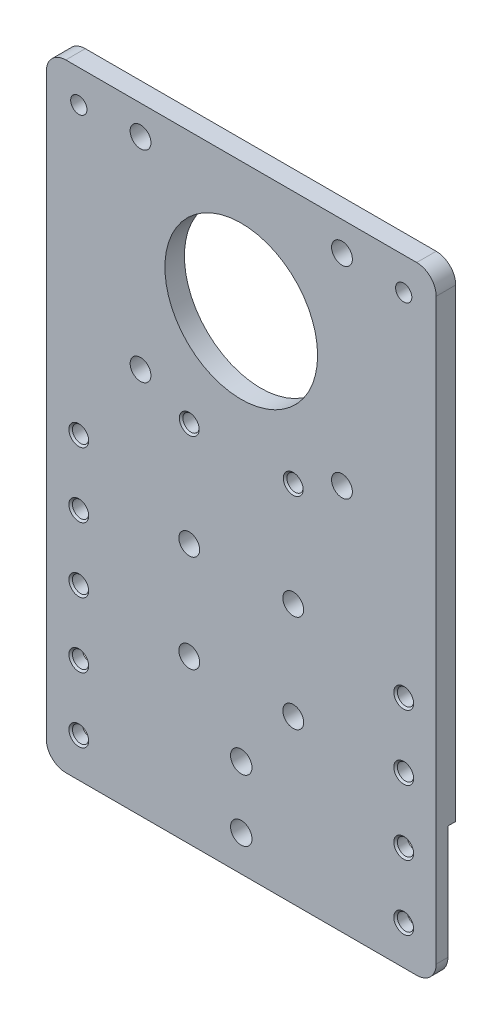
SolidWorks part; units mm, degrees
ref_plane "前视基准面" through (0, 0, 0) normal (0, 0, 1) x (1, 0, 0)
ref_plane "上视基准面" through (0, 0, 0) normal (0, 1, 0) x (1, 0, 0)
ref_plane "右视基准面" through (0, 0, 0) normal (1, 0, 0) x (0, 0, -1)
sketch "草图1" plane through (0, 0, 0) normal (0, 0, 1) x (1, 0, 0)
  line L0 (-30, -25) -> (-30, -67)
  line L1 (-27, 25) -> (27, 25)
  line L2 (-30, 22) -> (-30, -25)
  line L3 (-27, -70) -> (27, -70)
  line L4 (30, 22) -> (30, -67)
  circle A6 centre (0, 5) radius 11.75
  circle A7 centre (15.5, 20.5) radius 1.6
  circle A8 centre (-15.5, 20.5) radius 1.6
  circle A9 centre (-15.5, -10.5) radius 1.6
  circle A10 centre (15.5, -10.5) radius 1.6
  arc A11 (-30, -67) -> (-27, -70) centre (-27, -67) ccw
  arc A12 (27, -70) -> (30, -67) centre (27, -67) ccw
  arc A13 (27, 25) -> (30, 22) centre (27, 22) cw
  arc A14 (-27, 25) -> (-30, 22) centre (-27, 22) ccw
  circle A15 centre (-8, -30) radius 1.6
  circle A16 centre (8, -30) radius 1.6
  circle A17 centre (-8, -45) radius 1.6
  circle A18 centre (8, -45) radius 1.6
  point P47 (-30, -70)
  point P52 (30, 25)
  point P55 (-30, 25)
  dimension "D14" = 23.5
  dimension "D17" = 3.2
  dimension "D22" = 3.2
  dimension "D23" = 3.2
  dimension "D24" = 3.2
  dimension "D25" = 3
  dimension "D26" = 3.2
  dimension "D1" = 95
  dimension "D2" = 60
  dimension "D3" = 25
  dimension "D4" = 30
  dimension "D16" = 20
  dimension "D18" = 15.5
  dimension "D19" = 15.5
  dimension "D20" = 31
  dimension "D21" = 31
  dimension "D27" = 16
  dimension "D28" = 15
  dimension "D29" = 8
  dimension "D30" = 55
extrude "凸台-拉伸1" add sketch "草图1" along normal blind 3
sketch "草图12" plane through (0, 0, 3) normal (0, 0, 1) x (1, 0, 0)
  line L0 (-27, -70) -> (27, -70) construction
  circle A0 centre (-25, -44) radius 1.6
  circle A1 centre (-25, -54) radius 1.6
  circle A2 centre (-25, -64) radius 1.6
  circle A3 centre (25, -44) radius 1.6
  circle A4 centre (25, -54) radius 1.6
  circle A5 centre (25, -64) radius 1.6
  circle A7 centre (-8, -14) radius 1.5369
  circle A9 centre (8, -14) radius 1.5369
  circle A11 centre (8, -30) radius 1.6 construction
  circle A12 centre (-8, -30) radius 1.6 construction
  circle A13 centre (8, -30) radius 1.6 construction
  circle A14 centre (-8, -30) radius 1.6 construction
  circle A15 centre (25, -34) radius 1.6
  circle A16 centre (-25, -34) radius 1.6
  circle A17 centre (-25, -24) radius 1.6
  point P0 (-25, -44)
  point P2 (-25, -54)
  point P4 (25, -44)
  point P6 (25, -54)
  point P8 (25, -64)
  point P10 (-25, -64)
  point P32 (-8, -14)
  point P37 (8, -14)
  point P49 (25, -34)
  point P53 (-25, -34)
  point P56 (-25, -24)
  dimension "D1" = 3.2
  dimension "D2" = 16
  dimension "D4" = 10
  dimension "D3" = 10
  dimension "D5" = 10
  dimension "D6" = 10
  dimension "D7" = 10
  dimension "D8" = 25
  dimension "D9" = 6
  dimension "D10" = 50
  dimension "D11" = 10
  dimension "D12" = 10
hole_wizard "M3x0.5 螺纹孔4" positions "草图12" profile "草图13" tap size "M3x0.5" standard "ANSI Metric" end condition through all
cosmetic thread "孔螺纹线19" parameters "D2"=3
cosmetic thread "孔螺纹线20" parameters "D2"=3
cosmetic thread "孔螺纹线21" parameters "D2"=3
cosmetic thread "孔螺纹线22" parameters "D2"=3
cosmetic thread "孔螺纹线23" parameters "D2"=3
cosmetic thread "孔螺纹线24" parameters "D2"=3
sketch "草图13" plane through (-25, -44, 3) normal (1, 0, 0) x (0, -1, 0)
  line L0 (0, 0) -> (0, 3)
  line L1 (0, 3) -> (1.25, 3)
  line L2 (1.25, 3) -> (1.25, 0.275)
  line L3 (1.25, 0.275) -> (1.525, 0)
  line L5 (1.525, 0) -> (0, 0)
  line L6 (-1.25, 0.275) -> (-1.525, 0) construction
  line L11 (0, -6.35) -> (0, 107.95) construction
  dimension "通孔螺纹孔钻头直径" = 2.5
  dimension "通孔螺纹孔钻头深度" = 3
  dimension "近端锥形沉头孔直径" = 3.05
  dimension "近端锥形沉头孔角度" = 90
cosmetic thread "孔螺纹线27" parameters "D2"=3
cosmetic thread "孔螺纹线28" parameters "D2"=3
cosmetic thread "孔螺纹线31" parameters "D2"=3
cosmetic thread "孔螺纹线32" parameters "D2"=3
cosmetic thread "孔螺纹线33" parameters "D2"=3
sketch "草图18" plane through (0, 0, 0) normal (0, 0, -1) x (-1, 0, 0)
  line L0 (-30, -67) -> (-30, 22) construction
  line L1 (27, -70) -> (-27, -70) construction
  point P0 (0, -55)
  point P3 (0, -64.5)
  dimension "D1" = 9.5
  dimension "D2" = 30
  dimension "D3" = 5.5
hole_wizard "M4x0.7 螺纹孔1" positions "草图18" profile "草图17" tap size "M4x0.7" standard "ANSI Metric" end condition through all
sketch "草图17" plane through (0, -55, 0) normal (1, 0, 0) x (0, 1, 0)
  line L0 (0, 0) -> (0, 3)
  line L1 (0, 3) -> (1.65, 3)
  line L2 (1.65, 3) -> (1.65, 0.375)
  line L3 (1.65, 0.375) -> (2.025, 0)
  line L5 (2.025, 0) -> (0, 0)
  line L6 (-1.65, 0.375) -> (-2.025, 0) construction
  line L11 (0, -6.35) -> (0, 107.95) construction
  dimension "通孔螺纹孔钻头直径" = 3.3
  dimension "通孔螺纹孔钻头深度" = 3
  dimension "近端锥形沉头孔直径" = 4.05
  dimension "近端锥形沉头孔角度" = 90
cosmetic thread "孔螺纹线25" parameters "D2"=4
cosmetic thread "孔螺纹线26" parameters "D2"=4
sketch "草图19" plane through (0, 0, 0) normal (0, 0, -1) x (-1, 0, 0)
  line L0 (-27, 25) -> (27, 25) construction
  line L1 (-30, -67) -> (-30, 22) construction
  line L2 (30, 22) -> (30, -67) construction
  circle A0 centre (-25, 20) radius 1.6
  circle A1 centre (25, 20) radius 1.6
  point P0 (-25, 20)
  point P2 (25, 20)
  dimension "D4" = 3.2
  dimension "D1" = 5
  dimension "D2" = 5
  dimension "D3" = 5
hole_wizard "M3x0.5 螺纹孔5" positions "草图19" profile "草图20" tap size "M3x0.5" standard "ANSI Metric" end condition through all
sketch "草图20" plane through (25, 20, 0) normal (1, 0, 0) x (0, 1, 0)
  line L0 (0, 0) -> (0, 3)
  line L1 (0, 3) -> (1.25, 3)
  line L2 (1.25, 3) -> (1.25, 0.275)
  line L3 (1.25, 0.275) -> (1.525, 0)
  line L5 (1.525, 0) -> (0, 0)
  line L6 (-1.25, 0.275) -> (-1.525, 0) construction
  line L11 (0, -6.35) -> (0, 107.95) construction
  dimension "通孔螺纹孔钻头直径" = 2.5
  dimension "通孔螺纹孔钻头深度" = 3
  dimension "近端锥形沉头孔直径" = 3.05
  dimension "近端锥形沉头孔角度" = 90
cosmetic thread "孔螺纹线34" parameters "D2"=3
cosmetic thread "孔螺纹线35" parameters "D2"=3
sketch "草图23" plane through (0, 0, 0) normal (0, 0, -1) x (-1, 0, 0)
  line L0 (-30, -67) -> (-30, 22) construction
  line L1 (-30, -49.5) -> (-20.4, -49.5)
  line L2 (-30, -49.5) -> (-30, -70)
  line L3 (-30, -70) -> (-20.4, -70)
  line L4 (30, -49.5) -> (30, -70)
  line L5 (30, 22) -> (30, -67) construction
  line L6 (27, -70) -> (-27, -70) construction
  line L7 (-20.4, -49.5) -> (-19.6, -49.5) construction
  line L8 (-20.4, -49.5) -> (-19.6, -49.5) construction
  line L9 (-20.4, -49.5) -> (-20.4, -70)
  line L10 (-20.4, -70) -> (-19.6, -70) construction
  line L11 (-19.6, -49.5) -> (-19.6, -70)
  line L12 (-17.2, -49.5) -> (-16.4, -49.5) construction
  line L13 (-17.2, -49.5) -> (-17.2, -70)
  line L14 (-17.2, -70) -> (-16.4, -70) construction
  line L15 (-16.4, -49.5) -> (-16.4, -70)
  line L16 (-19.6, -49.5) -> (-17.2, -49.5)
  line L17 (-17.2, -49.5) -> (-16.4, -49.5) construction
  line L18 (-16.4, -49.5) -> (-14, -49.5)
  line L19 (-20.4, -70) -> (-19.6, -70) construction
  line L20 (-19.6, -70) -> (-17.2, -70)
  line L21 (-17.2, -70) -> (-16.4, -70) construction
  line L22 (-16.4, -70) -> (-14, -70)
  line L23 (-10, -49.5) -> (10, -70) construction
  line L24 (-14, -49.5) -> (-13.2, -49.5) construction
  line L25 (-14, -49.5) -> (-14, -70)
  line L26 (-14, -70) -> (-13.2, -70) construction
  line L27 (-13.2, -49.5) -> (-13.2, -70)
  line L28 (-10.8, -49.5) -> (-10, -49.5) construction
  line L29 (-10.8, -49.5) -> (-10.8, -70)
  line L30 (-10.8, -70) -> (-10, -70) construction
  line L31 (-10, -49.5) -> (-10, -70)
  line L32 (10.8, -49.5) -> (10, -49.5) construction
  line L33 (10.8, -49.5) -> (10.8, -70)
  line L34 (10.8, -70) -> (10, -70) construction
  line L35 (10, -49.5) -> (10, -70)
  line L36 (13.2, -70) -> (14, -70) construction
  line L37 (13.2, -70) -> (13.2, -49.5)
  line L38 (13.2, -49.5) -> (14, -49.5) construction
  line L39 (14, -70) -> (14, -49.5)
  line L40 (17.2, -49.5) -> (16.4, -49.5) construction
  line L41 (17.2, -49.5) -> (17.2, -70)
  line L42 (17.2, -70) -> (16.4, -70) construction
  line L43 (16.4, -49.5) -> (16.4, -70)
  line L44 (19.6, -70) -> (20.4, -70) construction
  line L45 (19.6, -70) -> (19.6, -49.5)
  line L46 (19.6, -49.5) -> (20.4, -49.5) construction
  line L47 (20.4, -70) -> (20.4, -49.5)
  line L48 (0, -55) -> (0, -64.5) construction
  line L49 (-14, -49.5) -> (-13.2, -49.5) construction
  line L50 (-13.2, -49.5) -> (-10.8, -49.5)
  line L51 (-10.8, -49.5) -> (-10, -49.5) construction
  line L52 (-10, -49.5) -> (-6, -49.5)
  line L53 (10, -49.5) -> (10.8, -49.5) construction
  line L54 (10.8, -49.5) -> (13.2, -49.5)
  line L55 (13.2, -49.5) -> (14, -49.5) construction
  line L56 (14, -49.5) -> (16.4, -49.5)
  line L57 (19.6, -70) -> (20.4, -70) construction
  line L58 (20.4, -70) -> (30, -70)
  line L59 (16.4, -70) -> (17.2, -70) construction
  line L60 (17.2, -70) -> (19.6, -70)
  line L61 (13.2, -70) -> (14, -70) construction
  line L62 (14, -70) -> (16.4, -70)
  line L63 (10, -70) -> (10.8, -70) construction
  line L64 (10.8, -70) -> (13.2, -70)
  line L65 (-10.8, -70) -> (-10, -70) construction
  line L66 (-10, -70) -> (-6, -70)
  line L67 (-14, -70) -> (-13.2, -70) construction
  line L68 (-13.2, -70) -> (-10.8, -70)
  line L69 (16.4, -49.5) -> (17.2, -49.5) construction
  line L70 (17.2, -49.5) -> (19.6, -49.5)
  line L71 (19.6, -49.5) -> (20.4, -49.5) construction
  line L72 (20.4, -49.5) -> (30, -49.5)
  line L73 (-6, -49.5) -> (6, -49.5) construction
  line L74 (-6, -49.5) -> (6, -49.5) construction
  line L75 (-6, -49.5) -> (-6, -70)
  line L76 (-6, -70) -> (6, -70) construction
  line L77 (6, -49.5) -> (6, -70)
  line L78 (-6, -49.5) -> (6, -70) construction
  line L79 (-6, -70) -> (6, -49.5) construction
  line L80 (6, -49.5) -> (10, -49.5)
  line L81 (-6, -70) -> (6, -70) construction
  line L82 (6, -70) -> (10, -70)
  point P46 (0, -59.75)
  point P47 (0, -59.75)
  point P52 (0, -59.75)
  point P53 (0, 0)
  dimension "D2" = 0.8
  dimension "D3" = 0.8
  dimension "D4" = 2.4
  dimension "D5" = 0.8
  dimension "D6" = 0.8
  dimension "D7" = 2.4
  dimension "D8" = 2.4
  dimension "D9" = 0.8
  dimension "D10" = 0.8
  dimension "D11" = 0.8
  dimension "D12" = 0.8
  dimension "D13" = 2.4
  dimension "D14" = 2.4
  dimension "D15" = 2.4
  dimension "D16" = 20
  dimension "D17" = 12
extrude "切除-拉伸4" cut sketch "草图23" against normal blind 1.2
fillet "圆角1" radius 0.6 18 edges at (-19.6, -49.5, 0.6) (-16.4, -49.5, 0.6) (-13.2, -49.5, 0.6) (-17.2, -49.5, 0.6) (-20.4, -49.5, 0.6) (-10.8, -49.5, 0.6) (-14, -49.5, 0.6) (10, -49.5, 0.6) (13.2, -49.5, 0.6) (16.4, -49.5, 0.6) (19.6, -49.5, 0.6) (10.8, -49.5, 0.6) (14, -49.5, 0.6) (17.2, -49.5, 0.6) (20.4, -49.5, 0.6) (6, -49.5, 0.6) (-6, -49.5, 0.6) (-10, -49.5, 0.6)
